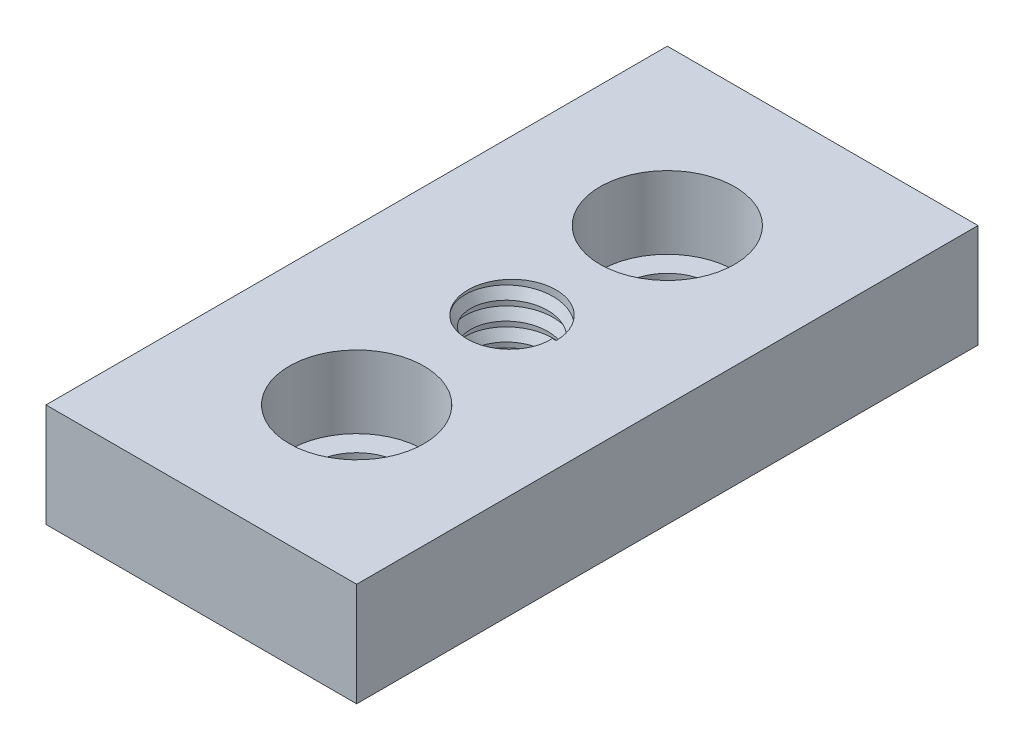
SolidWorks part; units mm, degrees
ref_plane "前视基准面" through (0, 0, 0) normal (0, 0, 1) x (1, 0, 0)
ref_plane "上视基准面" through (0, 0, 0) normal (0, 1, 0) x (1, 0, 0)
ref_plane "右视基准面" through (0, 0, 0) normal (1, 0, 0) x (0, 0, -1)
sketch "草图1" plane through (0, 0, 0) normal (0, 1, 0) x (1, 0, 0)
  line B0 (-15, -30) -> (15, -30)
  line B1 (15, -30) -> (15, 30)
  line B2 (15, 30) -> (-15, 30)
  line B3 (-15, 30) -> (-15, -30)
  circle B4 centre (0, 15) radius 4.25
  circle B5 centre (0, -15) radius 4.25
  circle B6 centre (0, 0) radius 4.25
sketch_block_instance "A$C2577602E-1"
sketch_block "A$C2577602E"
extrude "凸台-拉伸1" add sketch "草图1" along normal blind 10
sketch "草图3" plane through (0, 10, 0) normal (0, 1, 0) x (1, 0, 0)
  circle A0 centre (0, 15) radius 6.5
  circle A1 centre (0, -15) radius 6.5
extrude "切除-拉伸1" cut sketch "草图3" against normal blind 7
sketch "草图4" plane through (0, 10, 0) normal (0, 1, 0) x (1, 0, 0)
  circle A0 centre (0, 0) radius 4.25
curve "螺旋线/涡状线1" pitch 1.75 height 10 turns 5.7143
ref_plane "基准面2" through (4.25, 10, 0) normal (0, -0.0654, 0.9979) x (1, 0, 0)
sketch "草图5" plane through (4.25, 10, 0) normal (0, -0.0654, 0.9979) x (1, 0, 0)
  line L1 (0, 0.6016) -> (-0.521, -0.3008)
  line L2 (-0.521, -0.3008) -> (0.521, -0.3008)
  line L3 (0.521, -0.3008) -> (0, 0.6016)
sweep "扫描1" add profiles "草图5" path "螺旋线/涡状线1"
sketch "草图6" plane through (0, 0, 30) normal (0, 0, 1) x (1, 0, 0)
  line L1 (-15, 10) -> (15, 10)
  line L2 (-15, 10) -> (-15, 19.2588)
  line L3 (-15, 19.2588) -> (15, 19.2588)
  line L4 (15, 10) -> (15, 19.2588)
  line L5 (-15, 0) -> (15, 0)
  line L6 (-15, 0) -> (-15, -12.6467)
  line L7 (-15, -12.6467) -> (15, -12.6467)
  line L8 (15, 0) -> (15, -12.6467)
extrude "切除-拉伸2" cut sketch "草图6" against normal through all
